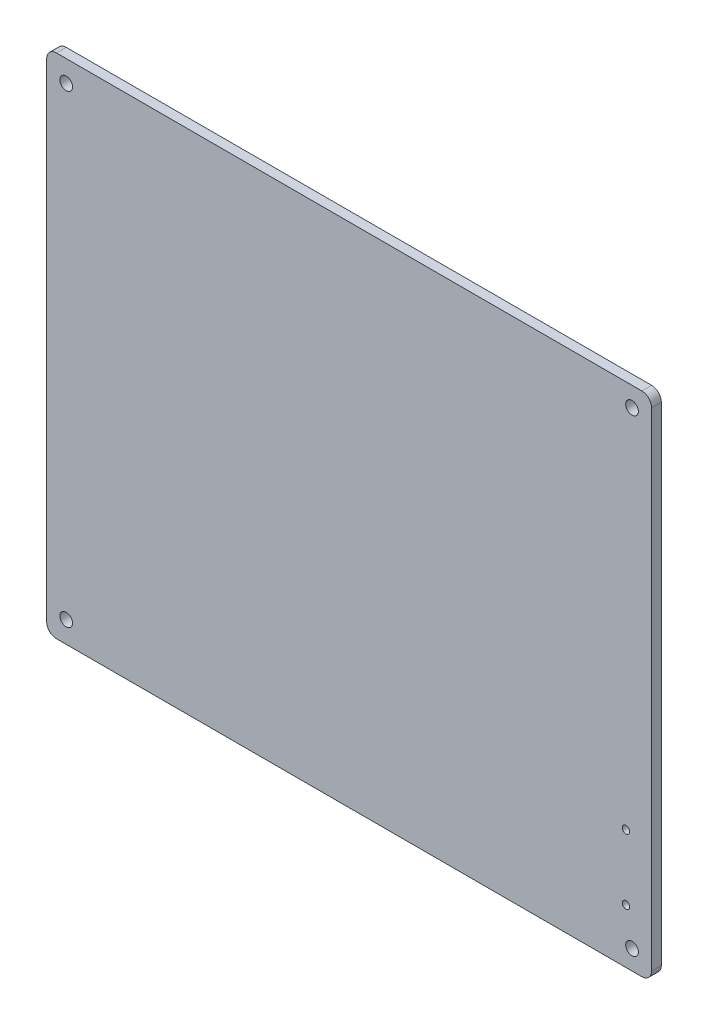
SolidWorks part; units mm, degrees
ref_plane "Front Plane" through (0, 0, 0) normal (0, 0, 1) x (1, 0, 0)
ref_plane "Top Plane" through (0, 0, 0) normal (0, 1, 0) x (1, 0, 0)
ref_plane "Right Plane" through (0, 0, 0) normal (1, 0, 0) x (0, 0, -1)
sketch "Sketch1" plane through (0, 0, 0) normal (0, 0, 1) x (1, 0, 0)
  line L1 (-295, -10) -> (5, -10)
  line L2 (-300, -5) -> (-300, 245)
  line L3 (-295, 250) -> (5, 250)
  line L4 (10, -5) -> (10, 245)
  circle A0 centre (0, 0) radius 3.25
  circle A1 centre (0, 240) radius 3.25
  circle A2 centre (-290, 239) radius 3.25
  circle A3 centre (-290, 1) radius 3.25
  circle A6 centre (-3.1, 17.7826) radius 1.9
  circle A7 centre (-3.1, 51.2174) radius 1.9
  arc A8 (-295, -10) -> (-300, -5) centre (-295, -5) cw
  arc A9 (5, -10) -> (10, -5) centre (5, -5) ccw
  arc A10 (5, 250) -> (10, 245) centre (5, 245) cw
  arc A11 (-300, 245) -> (-295, 250) centre (-295, 245) cw
  dimension "D1" = 5
extrude "Boss-Extrude1" add sketch "Sketch1" along normal blind 5
